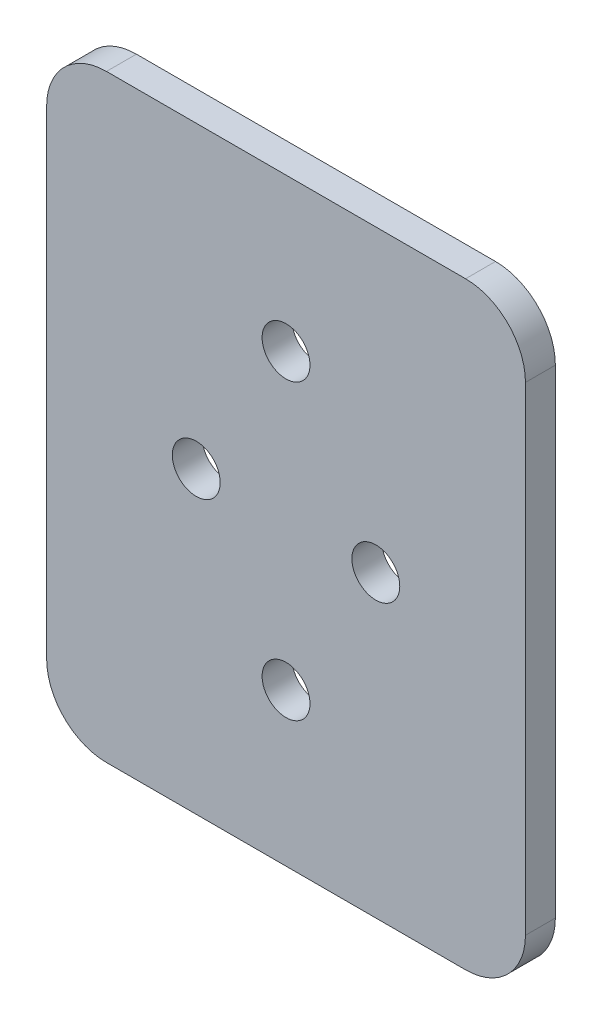
SolidWorks part; units mm, degrees
ref_plane "Ön Düzlem" through (0, 0, 0) normal (0, 0, 1) x (1, 0, 0)
ref_plane "Üst Düzlem" through (0, 0, 0) normal (0, 1, 0) x (1, 0, 0)
ref_plane "Sağ Düzlem" through (0, 0, 0) normal (1, 0, 0) x (0, 0, -1)
sketch "Çizim1" plane through (0, 0, 0) normal (0, 0, 1) x (1, 0, 0)
  line L1 (30, -50) -> (-30, -50)
  line L2 (40, -40) -> (40, 40)
  line L3 (30, 50) -> (-30, 50)
  line L4 (-40, -40) -> (-40, 40)
  circle A0 centre (0, 24.5) radius 4
  circle A1 centre (0, -24.5) radius 4
  circle A2 centre (-15, 0) radius 4
  circle A3 centre (15, 0) radius 4
  arc A4 (-40, -40) -> (-30, -50) centre (-30, -40) ccw
  arc A5 (30, -50) -> (40, -40) centre (30, -40) ccw
  arc A6 (30, 50) -> (40, 40) centre (30, 40) cw
  arc A7 (-40, 40) -> (-30, 50) centre (-30, 40) cw
  point P15 (-40, -50)
  point P18 (40, -50)
  point P23 (-40, 50)
  dimension "D1" = 49
  dimension "D2" = 8
  dimension "D3" = 8
  dimension "D4" = 30
  dimension "D5" = 15
  dimension "D6" = 8
  dimension "D7" = 8
  dimension "D12" = 10
  dimension "D13" = 25.5
  dimension "D8" = 50
  dimension "D9" = 40
  dimension "D10" = 80
  dimension "D11" = 100
extrude "Yükseklik-Ekstrüzyon1" add sketch "Çizim1" along normal blind 5
